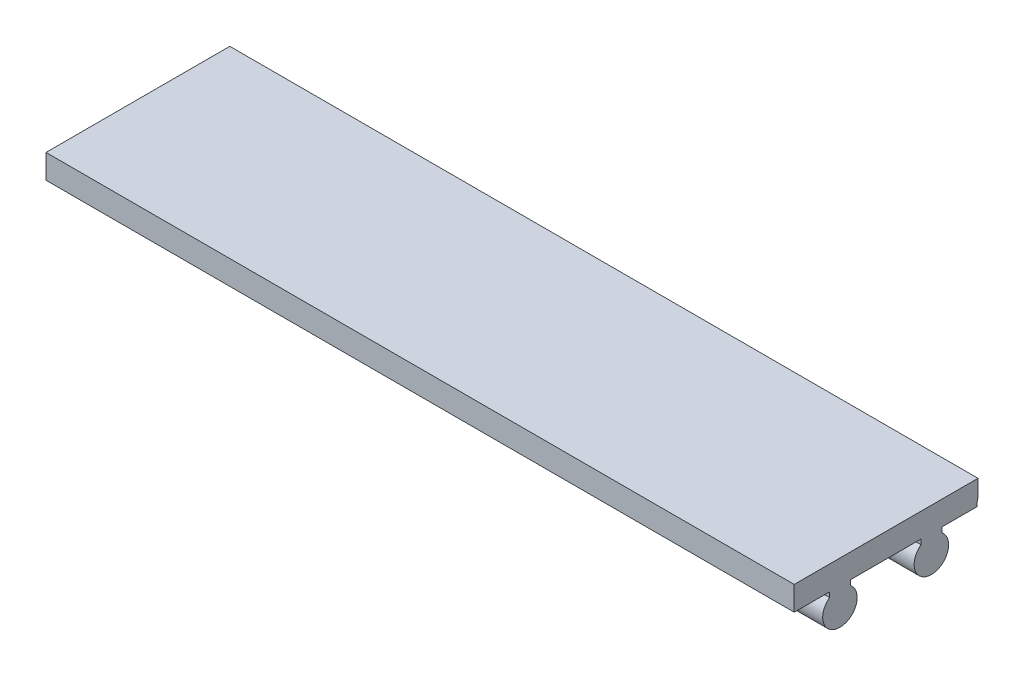
SolidWorks part; units mm, degrees
ref_plane "Спереди" through (0, 0, 0) normal (0, 0, 1) x (1, 0, 0)
ref_plane "Сверху" through (0, 0, 0) normal (0, 1, 0) x (1, 0, 0)
ref_plane "Справа" through (0, 0, 0) normal (1, 0, 0) x (0, 0, -1)
ref_plane "Плоскость4" through (90, 0, 0) normal (1, 0, 0) x (0, 0, -1)
sketch "Эскиз1" plane through (90, 0, 0) normal (1, 0, 0) x (0, 0, -1)
  line L0 (6.75, -24.0938) -> (6.75, 19.25)
  line L1 (6.75, 19.25) -> (-11.5938, 19.25)
  line L2 (-11.5938, 16.75) -> (-11, 16.75)
  line L3 (-11, 16.75) -> (-11, -16.75)
  line L4 (-11, -16.75) -> (-11.5938, -16.75)
  line L5 (-11.5938, -19.25) -> (-11, -19.25)
  line L6 (-11, -19.25) -> (-11, -23.5)
  line L7 (-11, -23.5) -> (-6.75, -23.5)
  line L8 (-6.75, -23.5) -> (-6.75, -24.0938)
  line L9 (-4.25, -24.0938) -> (-4.25, -23.5)
  line L10 (-4.25, -23.5) -> (4.25, -23.5)
  line L11 (4.25, -23.5) -> (4.25, -24.0938)
  arc A0 (-11.5938, 19.25) -> (-11.5938, 16.75) centre (-13.25, 18) ccw
  arc A1 (-11.5938, -16.75) -> (-11.5938, -19.25) centre (-13.25, -18) ccw
  arc A2 (-6.75, -24.0938) -> (-4.25, -24.0938) centre (-5.5, -25.75) ccw
  arc A3 (4.25, -24.0938) -> (6.75, -24.0938) centre (5.5, -25.75) ccw
extrude "Бобышка-Вытянуть1" add sketch "Эскиз1" against normal blind 90
sketch "Эскиз2" plane through (0, 19.25, 0) normal (0, 1, 0) x (-1, 0, 0)
  line L0 (-90, -6.75) -> (-90, 11)
  line L1 (-90, 11) -> (0, 11)
  line L2 (0, 11) -> (0, -6.75)
  line L3 (0, -6.75) -> (-90, -6.75)
extrude "Бобышка-Вытянуть2" add sketch "Эскиз2" along normal blind 8.2
sketch "Эскиз3" plane through (0, 0, -6.75) normal (0, 0, -1) x (-1, 0, 0)
  line L0 (0, -23.5) -> (-90, -23.5)
  line L1 (-90, -23.5) -> (-90, 27.45)
  line L2 (-90, 27.45) -> (0, 27.45)
  line L3 (0, 27.45) -> (0, -23.5)
extrude "Бобышка-Вытянуть3" add sketch "Эскиз3" along normal blind 8.2
sketch "Эскиз4" plane through (0, 0, 0) normal (-1, 0, 0) x (0, 0, 1)
  line L0 (-14.95, -14.75) -> (-11, -14.75)
  line L1 (-11, -14.75) -> (-11, 14.75)
  line L2 (-11, 14.75) -> (-14.95, 14.75)
  line L3 (-14.95, 14.75) -> (-14.95, -14.75)
extrude "Вырез-Вытянуть1" cut sketch "Эскиз4" against normal through all
sketch "Эскиз5" plane through (0, 0, 0) normal (-1, 0, 0) x (0, 0, 1)
  line L0 (-14.95, 27.45) -> (-14.95, 21.25)
  line L1 (-14.95, 21.25) -> (-11, 21.25)
  line L2 (-11, 21.25) -> (-11, 27.45)
  line L3 (-11, 27.45) -> (-14.95, 27.45)
extrude "Вырез-Вытянуть2" cut sketch "Эскиз5" against normal through all
sketch "Эскиз6" plane through (0, 0, 0) normal (-1, 0, 0) x (0, 0, 1)
  line L0 (-11, 27.45) -> (-11, 23.5)
  line L1 (-11, 23.5) -> (-8.75, 23.5)
  line L2 (-8.75, 23.5) -> (-8.75, 27.45)
  line L3 (-8.75, 27.45) -> (-11, 27.45)
extrude "Вырез-Вытянуть3" cut sketch "Эскиз6" against normal through all
sketch "Эскиз7" plane through (0, 0, 0) normal (-1, 0, 0) x (0, 0, 1)
  line L0 (-2.25, 27.45) -> (-2.25, 23.5)
  line L1 (-2.25, 23.5) -> (2.25, 23.5)
  line L2 (2.25, 23.5) -> (2.25, 27.45)
  line L3 (2.25, 27.45) -> (-2.25, 27.45)
extrude "Вырез-Вытянуть4" cut sketch "Эскиз7" against normal through all
sketch "Эскиз8" plane through (0, 0, 0) normal (-1, 0, 0) x (0, 0, 1)
  line L0 (11, 27.45) -> (8.75, 27.45)
  line L1 (8.75, 27.45) -> (8.75, 23.5)
  line L2 (8.75, 23.5) -> (11, 23.5)
  line L3 (11, 23.5) -> (11, 27.45)
extrude "Вырез-Вытянуть5" cut sketch "Эскиз8" against normal through all
sketch "Эскиз9" plane through (0, 0, 0) normal (-1, 0, 0) x (0, 0, 1)
  line L0 (-14.95, -23.5) -> (-11, -23.5)
  line L1 (-11, -23.5) -> (-11, -21.25)
  line L2 (-11, -21.25) -> (-14.95, -21.25)
  line L3 (-14.95, -21.25) -> (-14.95, -23.5)
extrude "Вырез-Вытянуть6" cut sketch "Эскиз9" against normal through all
sketch "Эскиз10" plane through (90, 0, 0) normal (1, 0, 0) x (0, 0, -1)
  line L0 (10.1, 22.6) -> (-10.1, 22.6)
  line L1 (-10.1, 22.6) -> (-10.1, -22.6)
  line L2 (-10.1, -22.6) -> (10.1, -22.6)
  line L3 (10.1, -22.6) -> (10.1, 22.6)
extrude "Вырез-Вытянуть7" cut sketch "Эскиз10" against normal blind 86
hole_wizard "Диаметр отверстия Ø2.5 (2.5)1" positions "Эскиз12" profile "Эскиз11" hole size "Ø2.5" standard "Ansi Metric"
sketch "Эскиз12" plane through (90, 0, 0) normal (1, 0, 0) x (0, 0, -1)
  point P0 (5.5, -25.75)
  point P1 (-13.25, -18)
  point P2 (-5.5, -25.75)
  point P3 (-13.25, 18)
sketch "Эскиз11" plane through (90, -25.75, -5.5) normal (0, 1, 0) x (0, 0, -1)
  line L0 (0, 0) -> (0, 90)
  line L1 (0, 90) -> (1.25, 90)
  line L2 (1.25, 90) -> (1.25, 0)
  line L5 (1.25, 0) -> (0, 0)
  line L11 (0, -6.35) -> (0, 107.95) construction
  dimension "Диаметр сквозного отверстия" = 2.5
  dimension "Глубина сквозного отверстия" = 90
hole_wizard "Диаметр отверстия Ø4.5 (4.5)1" positions "Эскиз14" profile "Эскиз13" hole size "Ø4.5" standard "Ansi Metric"
sketch "Эскиз14" plane through (0, 0, 0) normal (-1, 0, 0) x (0, 0, 1)
  point P0 (-13.25, -18)
  point P1 (-13.25, 18)
  point P2 (-5.5, 25.75)
  point P3 (5.5, 25.75)
sketch "Эскиз13" plane through (0, -18, -13.25) normal (0, 1, 0) x (0, 0, 1)
  line L0 (0, 0) -> (0, 90)
  line L1 (0, 90) -> (2.25, 90)
  line L2 (2.25, 90) -> (2.25, 0)
  line L5 (2.25, 0) -> (0, 0)
  line L11 (0, -6.35) -> (0, 107.95) construction
  dimension "Диаметр сквозного отверстия" = 4.5
  dimension "Глубина сквозного отверстия" = 90
hole_wizard "Диаметр отверстия Ø8.3 (8.3)1" positions "Эскиз16" profile "Эскиз15" hole size "Ø8.3" standard "Ansi Metric"
sketch "Эскиз16" plane through (0, 0, 0) normal (-1, 0, 0) x (0, 0, 1)
  point P0 (0, 0)
sketch "Эскиз15" plane through (0, 0, 0) normal (0, 1, 0) x (0, 0, 1)
  line L0 (0, 0) -> (0, 3.2)
  line L1 (0, 3.2) -> (4.15, 3.2)
  line L2 (4.15, 3.2) -> (4.15, 0)
  line L5 (4.15, 0) -> (0, 0)
  line L10 (0, 3.2) -> (-4.15, 3.2) construction
  line L11 (0, -6.35) -> (0, 107.95) construction
  dimension "Диаметр отверстия" = 8.3
  dimension "Глубина отверстия" = 3.2
  dimension "Угол заточки сверла" = 180
fillet "Скругление1" radius 2 1 edges at (45, 23.5, 8.75)
fillet "Скругление2" radius 2 11 edges at (4, -22.6, 0) (4, 0, -10.1) (4, 0, 10.1) (4, 22.6, 0) (45, -21.25, -11) (45, -14.75, -11) (45, 14.75, -11) (45, 21.25, -11) (45, 23.5, -8.75) (45, 23.5, -2.25) (45, 23.5, 2.25)
sketch "Эскиз17" plane through (90, 0, 0) normal (1, 0, 0) x (0, 0, -1)
  circle A0 centre (5.5, -25.75) radius 1.25 construction
  circle A1 centre (-5.5, -25.75) radius 1.25 construction
  circle A2 centre (-13.25, -18) radius 1.25 construction
  circle A3 centre (-13.25, 18) radius 1.25 construction
  circle A4 centre (5.5, -25.75) radius 1.25
  circle A5 centre (-5.5, -25.75) radius 1.25
  circle A6 centre (-13.25, -18) radius 1.25
  circle A7 centre (-13.25, 18) radius 1.25
extrude "Бобышка-Вытянуть4" add sketch "Эскиз17" against normal blind 90
sketch "Эскиз18" plane through (0, 0, 0) normal (-1, 0, 0) x (0, 0, 1)
  circle A0 centre (0, 0) radius 4.15 construction
  circle A1 centre (0, 0) radius 4.15
extrude "Вырез-Вытянуть8" cut sketch "Эскиз18" against normal blind 100
sketch "Эскиз19" plane through (90, 0, 0) normal (1, 0, 0) x (0, 0, -1)
  line L0 (10.1, -22.6) -> (-10.1, -22.6) construction
  line L1 (10.1, -22.6) -> (-10.1, -22.6)
  line L2 (10.1, -22.6) -> (29.6278, -22.6)
  line L3 (-10.1, -22.6) -> (-27.0285, -22.6)
  line L4 (-27.0285, -22.6) -> (-27.0285, 40.2916)
  line L5 (-27.0285, 40.2916) -> (29.6278, 40.2916)
  line L6 (29.6278, 40.2916) -> (29.6278, -22.6)
extrude "Вырез-Вытянуть9" cut sketch "Эскиз19" against normal blind 106
sketch "Эскиз20" plane through (0, -22.6, 0) normal (0, 1, 0) x (1, 0, 0)
  line L4 (90, -11) -> (90, 11.1086)
  line L5 (90, 11.1086) -> (0, 11.1086)
  line L6 (0, 11.1086) -> (0, -11)
  line L7 (0, -11) -> (90, -11)
  line L8 (90, -11) -> (90, 11.1086)
  line L9 (90, 11.1086) -> (0, 11.1086)
  line L10 (0, 11.1086) -> (0, -11)
  line L11 (0, -11) -> (90, -11)
  dimension "D1" = 0
extrude "Бобышка-Вытянуть5" add sketch "Эскиз20" along normal blind 2
